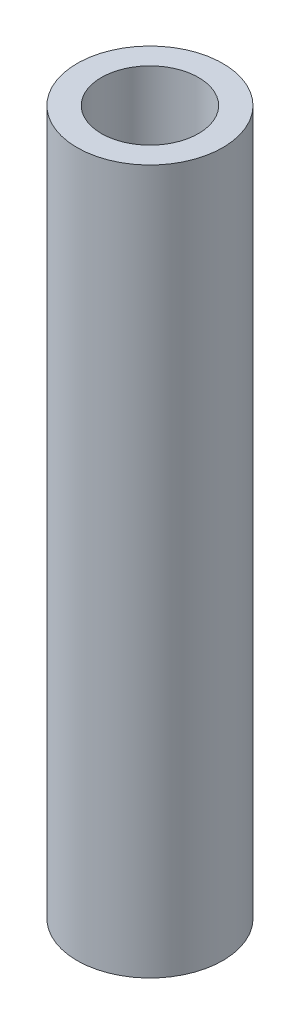
SolidWorks part; units mm, degrees
material "Fr-4"
ref_plane "Front Plane" through (0, 0, 0) normal (0, 0, 1) x (1, 0, 0)
ref_plane "Top Plane" through (0, 0, 0) normal (0, 1, 0) x (1, 0, 0)
ref_plane "Right Plane" through (0, 0, 0) normal (1, 0, 0) x (0, 0, -1)
sketch "Sketch1" plane through (0, 0, 0) normal (0, 1, 0) x (1, 0, 0)
  circle A0 centre (0, 0) radius 4.7625
  circle A1 centre (0, 0) radius 3.175
  dimension "D1" = 9.525
  dimension "D2" = 6.35
extrude "Boss-Extrude1" add sketch "Sketch1" along normal blind 46
ref_plane "Plane1" through (0, 0, 0) normal (0, -1, 0) x (-1, 0, 0)
sketch "Sketch2" plane through (0, 0, 0) normal (0, -1, 0) x (-1, 0, 0)
  point P0 (0, 0)
ref_plane "Plane2" through (0, 46, 0) normal (0, 1, 0) x (1, 0, 0)
sketch "Sketch4" plane through (0, 46, 0) normal (0, 1, 0) x (1, 0, 0)
  point P0 (0, 0)
